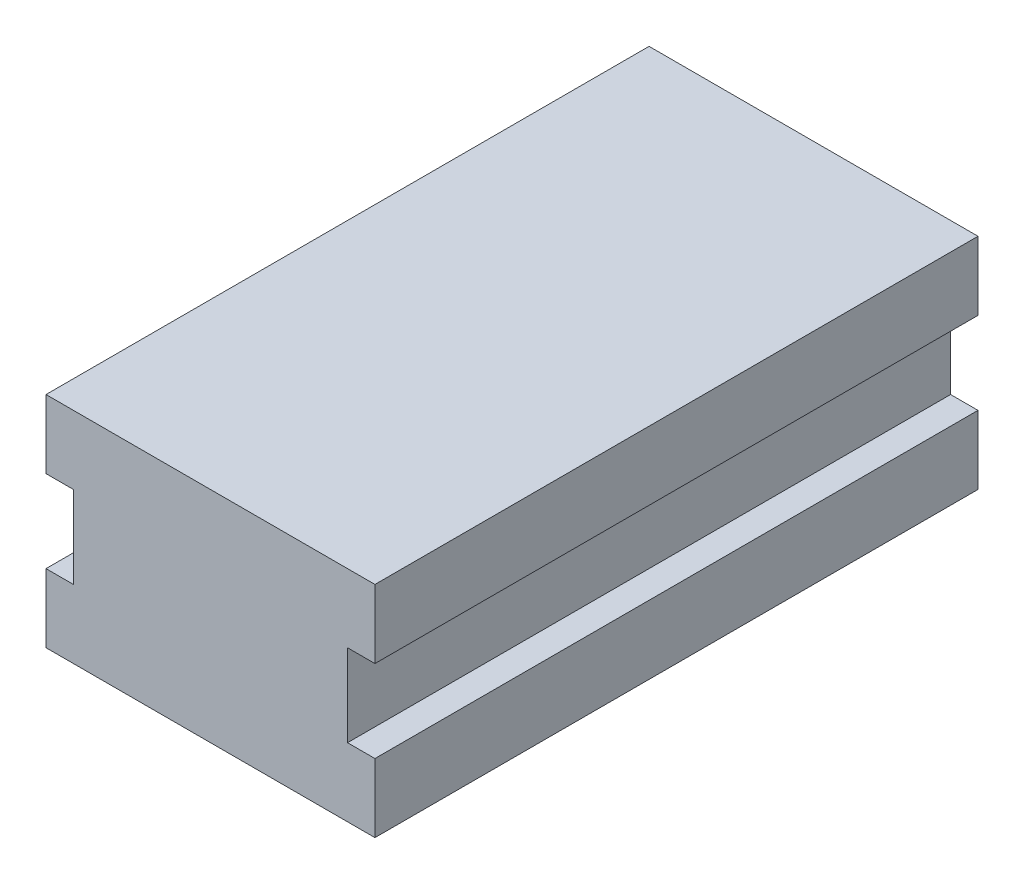
SolidWorks part; units mm, degrees
ref_plane "Front Plane" through (0, 0, 0) normal (0, 0, 1) x (1, 0, 0)
ref_plane "Top Plane" through (0, 0, 0) normal (0, 1, 0) x (1, 0, 0)
ref_plane "Right Plane" through (0, 0, 0) normal (1, 0, 0) x (0, 0, -1)
sketch "Sketch1" plane through (0, 0, 0) normal (0, 0, 1) x (1, 0, 0)
  line L0 (12, 8) -> (12, 5.5)
  line L1 (0, 0) -> (12, 0)
  line L3 (0, 8) -> (12, 8)
  line L4 (12, 5.5) -> (11, 5.5)
  line L5 (11, 5.5) -> (11, 2.5)
  line L6 (11, 2.5) -> (12, 2.5)
  line L7 (12, 2.5) -> (12, 0)
  line L8 (0, 8) -> (0, 5.5)
  line L9 (0, 5.5) -> (1, 5.5)
  line L10 (1, 5.5) -> (1, 2.5)
  line L11 (1, 2.5) -> (0, 2.5)
  line L12 (0, 2.5) -> (0, 0)
  dimension "D1" = 12
  dimension "D2" = 8
  dimension "D3" = 1
  dimension "D4" = 2.5
extrude "Boss-Extrude1" add sketch "Sketch1" along normal blind 22
